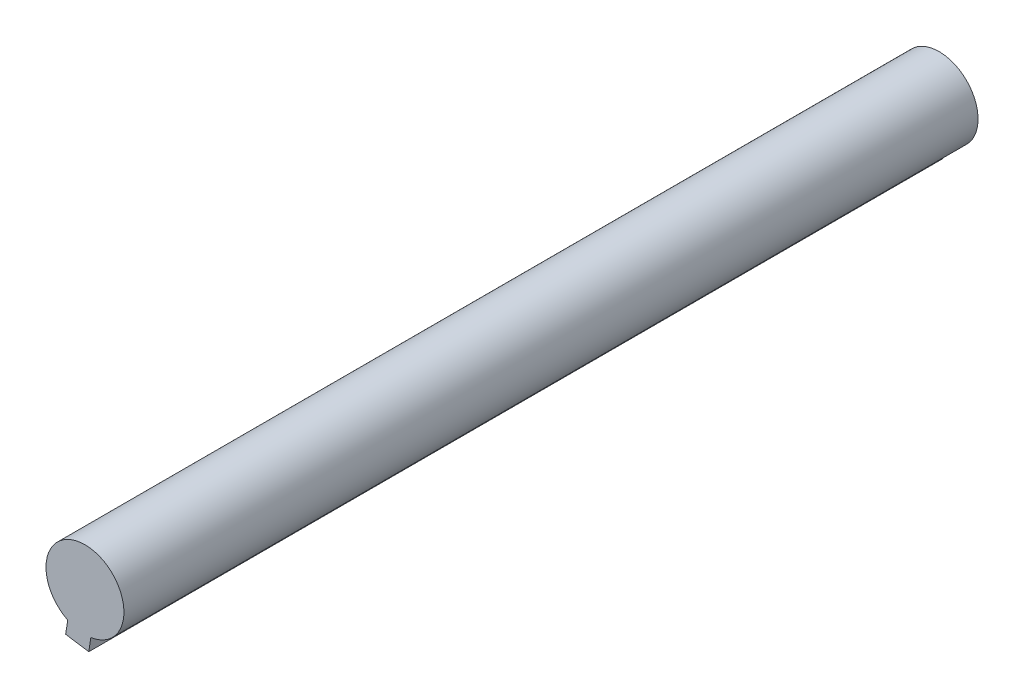
SolidWorks part; units mm, degrees
ref_plane "Front Plane" through (0, 0, 0) normal (0, 0, 1) x (1, 0, 0)
ref_plane "Top Plane" through (0, 0, 0) normal (0, 1, 0) x (1, 0, 0)
ref_plane "Right Plane" through (0, 0, 0) normal (1, 0, 0) x (0, 0, -1)
sketch "Sketch1" plane through (0, 0, 0) normal (0, 0, 1) x (1, 0, 0)
  line L0 (-3.5123, -7.1181) -> (-3.9327, -9.8326) construction
  line L5 (0.7736, -10.5617) -> (1.1941, -7.8472) construction
  line L6 (-3.9327, -9.8326) -> (0.7736, -10.5617) construction
  line L7 (-3.5123, -7.1181) -> (-3.9327, -9.8326)
  line L8 (0.7736, -10.5617) -> (1.1941, -7.8472)
  line L9 (-3.9327, -9.8326) -> (0.7736, -10.5617)
  arc A1 (1.1941, -7.8472) -> (-3.5123, -7.1181) centre (0, 0) ccw construction
  arc A2 (1.1941, -7.8472) -> (-3.5123, -7.1181) centre (0, 0) ccw
extrude "Boss-Extrude1" add sketch "Sketch1" along normal blind 173.99
